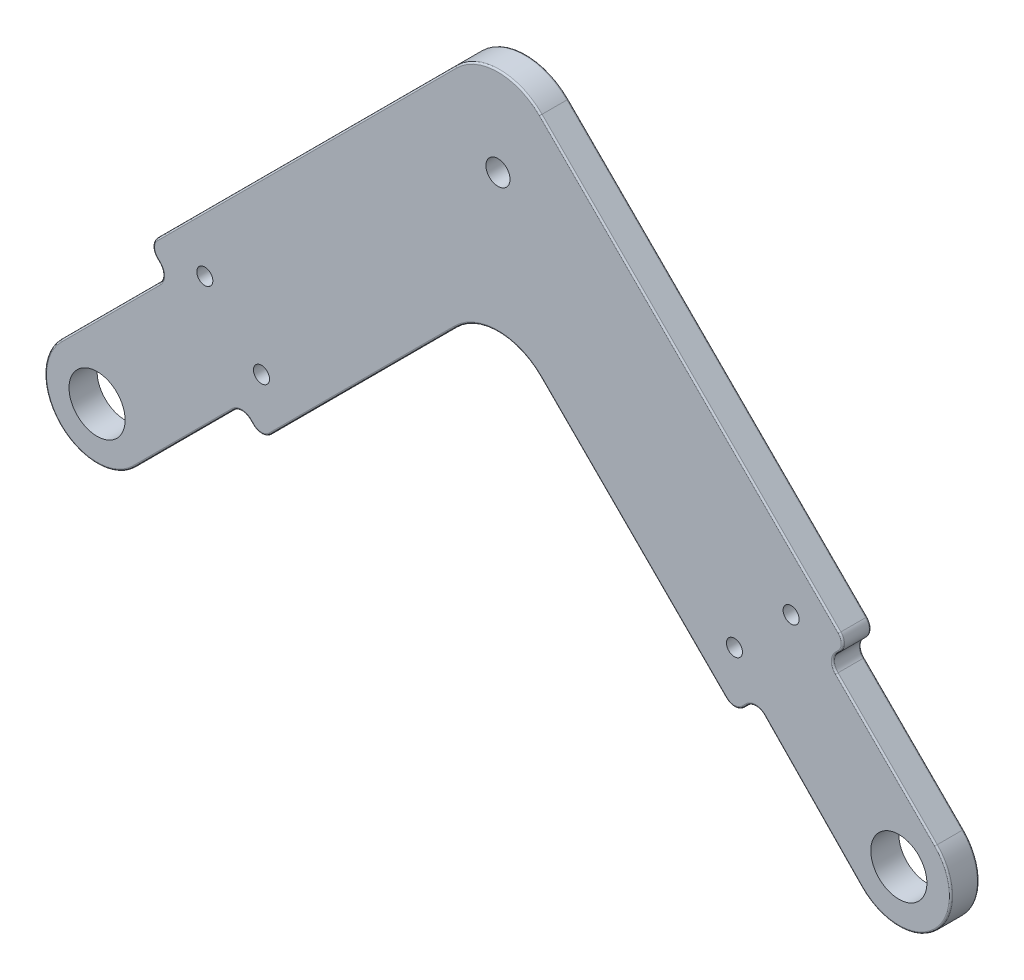
SolidWorks part; units mm, degrees
ref_plane "Front Plane" through (0, 0, 0) normal (0, 0, 1) x (1, 0, 0)
ref_plane "Top Plane" through (0, 0, 0) normal (0, 1, 0) x (1, 0, 0)
ref_plane "Right Plane" through (0, 0, 0) normal (1, 0, 0) x (0, 0, -1)
sketch "Sketch1" plane through (0, 0, 0) normal (0, 0, 1) x (1, 0, 0)
  line L0 (-100, 0) -> (100, 0) construction
  line L1 (-100, 0) -> (0, 100) construction
  line L2 (0, 100) -> (100, 0) construction
  line L3 (0, 0) -> (-50, 50) construction
  line L4 (-40, 60) -> (40, 60) construction
  line L5 (0, 100) -> (0, 60) construction
  circle A0 centre (-100, 0) radius 20
  circle A1 centre (0, 0) radius 20
  circle A2 centre (100, 0) radius 20
  point P4 (0, 0)
  dimension "D5" = 40
  dimension "D1" = 200
  dimension "D2" = 90
  dimension "D3" = 90
  dimension "D4" = 80
sketch "Sketch2" plane through (0, 0, 0) normal (0, 0, 1) x (1, 0, 0)
  line L0 (-56.5165, 43.4835) -> (-40, 60) construction
  line L1 (-100, 0) -> (0, 100) construction
  line L2 (-40, 60) -> (40, 60) construction
  line L3 (40, 60) -> (86.565, 13.435) construction
  line L4 (0, 100) -> (100, 0) construction
  line L5 (-49.4454, 36.4124) -> (-35.8579, 50)
  line L6 (-35.8579, 50) -> (35.8579, 50)
  line L7 (35.8579, 50) -> (79.4939, 6.364)
  line L8 (-63.5876, 50.5546) -> (-44.1421, 70)
  line L9 (-44.1421, 70) -> (44.1421, 70)
  line L10 (44.1421, 70) -> (93.636, 20.5061)
  line L11 (-63.5876, 50.5546) -> (-49.4454, 36.4124)
  line L12 (93.636, 20.5061) -> (79.4939, 6.364)
  line L13 (91.1612, 18.0312) -> (104.5962, 4.5962)
  line L14 (81.9688, 8.8388) -> (95.4038, -4.5962)
  line L15 (75.9584, 9.8995) -> (90.1005, 24.0416) construction
  line L16 (0, 100) -> (0, 60) construction
  line L17 (-6, 70) -> (-3.4304, 82.6944)
  line L18 (6, 70) -> (3.4304, 82.6944)
  circle A0 centre (100, 0) radius 3.5
  circle A1 centre (100, 0) radius 10 construction
  arc A2 (95.4038, -4.5962) -> (104.5962, 4.5962) centre (100, 0) ccw
  circle A3 centre (79.4939, 13.435) radius 1
  circle A4 centre (100, 0) radius 6.5 construction
  circle A5 centre (86.565, 20.5061) radius 1
  circle A6 centre (0, 60) radius 1.5
  circle A7 centre (0, 82) radius 1.5
  arc A8 (3.4304, 82.6944) -> (-3.4304, 82.6944) centre (0, 82) ccw
  circle A9 centre (-50, 50) radius 1.5
  circle A10 centre (0, 82) radius 3.5 construction
  point P25 (106.5, 0)
  point P47 (3.5, 82)
  dimension "D4" = 7
  dimension "D5" = 20
  dimension "D9" = 2
  dimension "D12" = 3
  dimension "D17" = 3
  dimension "D3" = 27.5
  dimension "D7" = 19
  dimension "D8" = 5
  dimension "D10" = 5
  dimension "D11" = 5
  dimension "D13" = 12
  dimension "D15" = 6
  dimension "D16" = 6
  dimension "D1" = 10
  dimension "D2" = 10
  dimension "D6" = 3
  dimension "D14" = 2
sketch "Sketch3" plane through (0, 0, 0) normal (0, 0, 1) x (1, 0, 0)
  line L0 (-100, 0) -> (100, 0) construction
  line L1 (-86.565, 13.435) -> (-50, 50) construction
  line L2 (-100, 0) -> (0, 100) construction
  line L3 (-50, 50) -> (-13.435, 13.435) construction
  line L4 (0, 0) -> (-50, 50) construction
  line L5 (-79.4939, 6.364) -> (-50, 35.8579)
  line L6 (-50, 35.8579) -> (-20.5061, 6.364)
  line L7 (-93.636, 20.5061) -> (-50, 64.1421)
  line L8 (-50, 64.1421) -> (-6.364, 20.5061)
  line L9 (-6.364, 20.5061) -> (-20.5061, 6.364)
  line L10 (-93.636, 20.5061) -> (-79.4939, 6.364)
  line L11 (-91.1612, 18.0312) -> (-104.5962, 4.5962)
  line L12 (-81.9688, 8.8388) -> (-95.4038, -4.5962)
  line L13 (-4.6576, -4.534) -> (-17.8509, 9.0191)
  line L14 (4.5962, 4.5962) -> (-8.8388, 18.0312)
  line L15 (-90.1005, 24.0416) -> (-75.9584, 9.8995) construction
  line L16 (-24.0416, 9.8995) -> (-9.8995, 24.0416) construction
  circle A0 centre (-100, 0) radius 3.5
  circle A1 centre (0, 0) radius 3.5
  circle A2 centre (-100, 0) radius 10 construction
  circle A3 centre (0, 0) radius 10 construction
  arc A4 (-4.6576, -4.534) -> (4.5962, 4.5962) centre (0, 0) ccw
  arc A5 (-104.5962, 4.5962) -> (-95.4038, -4.5962) centre (-100, 0) ccw
  circle A6 centre (0, 0) radius 20 construction
  circle A7 centre (-100, 0) radius 6.5 construction
  circle A8 centre (-86.565, 20.5061) radius 1
  circle A9 centre (0, 0) radius 6.5 construction
  circle A10 centre (-79.4939, 13.435) radius 1
  circle A11 centre (-20.5061, 13.435) radius 1
  circle A12 centre (-13.435, 20.5061) radius 1
  point P28 (-93.5, 0)
  point P36 (6.5, 0)
  dimension "D1" = 20
  dimension "D2" = 7
  dimension "D8" = 2
  dimension "D12" = 2
  dimension "D6" = 19
  dimension "D7" = 19
  dimension "D9" = 5
  dimension "D10" = 5
  dimension "D11" = 5
  dimension "D13" = 5
  dimension "D14" = 5
  dimension "D15" = 5
  dimension "D3" = 3
  dimension "D4" = 10
  dimension "D5" = 10
sketch "Sketch4" plane through (0, 0, 0) normal (0, 0, 1) x (1, 0, 0)
  line L0 (-57.5, 90.5) -> (57.5, 90.5)
  line L1 (4, 60) -> (4, 70)
  line L2 (57.5, 90.5) -> (57.5, 80.5)
  line L3 (57.5, 80.5) -> (44.1421, 70)
  line L4 (-44.1421, 70) -> (-57.5, 80.5)
  line L5 (-57.5, 80.5) -> (-57.5, 90.5)
  line L6 (-44.1421, 70) -> (44.1421, 70) construction
  line L7 (-4, 60) -> (-4, 70)
  line L8 (-22.5, 82) -> (22.5, 82) construction
  line L9 (-22.5, 86.5) -> (22.5, 86.5)
  line L10 (-22.5, 77.5) -> (22.5, 77.5)
  circle A2 centre (0, 60) radius 4
  arc A3 (-4, 60) -> (4, 60) centre (0, 60) ccw
  arc A4 (-22.5, 86.5) -> (-22.5, 77.5) centre (-22.5, 82) ccw
  arc A5 (22.5, 77.5) -> (22.5, 86.5) centre (22.5, 82) ccw
  point P4 (0, 100)
  point P14 (0, 82)
  point P27 (0, 90.5)
  dimension "D5" = 9
  dimension "D1" = 115
  dimension "D2" = 10
  dimension "D4" = 45
  dimension "D6" = 4
  dimension "D3" = 2.5
sketch "Sketch5" plane through (0, 0, 0) normal (0, 0, 1) x (1, 0, 0)
  line L0 (-91.1612, 18.0312) -> (-104.5962, 4.5962) construction
  line L1 (-81.9688, 8.8388) -> (-95.4038, -4.5962) construction
  line L2 (4.5962, 4.5962) -> (-8.8388, 18.0312) construction
  line L3 (-4.6576, -4.534) -> (-17.8509, 9.0191) construction
  line L4 (-91.1612, 18.0312) -> (-104.5962, 4.5962)
  line L5 (-81.9688, 8.8388) -> (-95.4038, -4.5962)
  line L6 (-79.4939, 6.364) -> (-50, 35.8579)
  line L7 (-50, 35.8579) -> (-20.5061, 6.364)
  line L8 (-20.5061, 6.364) -> (-6.364, 20.5061)
  line L9 (-6.364, 20.5061) -> (-50, 64.1421)
  line L10 (-50, 64.1421) -> (-93.636, 20.5061)
  line L11 (-93.636, 20.5061) -> (-79.4939, 6.364)
  line L12 (-79.4939, 6.364) -> (-50, 35.8579)
  line L13 (-50, 35.8579) -> (-20.5061, 6.364)
  line L14 (-20.5061, 6.364) -> (-17.8509, 9.0191)
  line L15 (-6.364, 20.5061) -> (-50, 64.1421)
  line L16 (-50, 64.1421) -> (-93.636, 20.5061)
  line L17 (-93.636, 20.5061) -> (-91.1612, 18.0312)
  line L18 (4.5962, 4.5962) -> (-8.8388, 18.0312)
  line L19 (-4.6576, -4.534) -> (-17.8509, 9.0191)
  line L20 (-81.9688, 8.8388) -> (-79.4939, 6.364)
  line L21 (-8.8388, 18.0312) -> (-6.364, 20.5061)
  arc A0 (-104.5962, 4.5962) -> (-95.4038, -4.5962) centre (-100, 0) ccw construction
  circle A1 centre (0, 0) radius 3.5
  circle A2 centre (0, 0) radius 3.5
  circle A3 centre (-100, 0) radius 3.5
  circle A4 centre (-100, 0) radius 3.5
  circle A5 centre (-79.4939, 13.435) radius 1
  circle A6 centre (-79.4939, 13.435) radius 1
  circle A7 centre (-86.565, 20.5061) radius 1
  circle A8 centre (-86.565, 20.5061) radius 1
  circle A9 centre (-13.435, 20.5061) radius 1
  circle A10 centre (-13.435, 20.5061) radius 1
  circle A11 centre (-20.5061, 13.435) radius 1
  circle A12 centre (-20.5061, 13.435) radius 1
  arc A13 (-4.6576, -4.534) -> (4.5962, 4.5962) centre (0, 0) ccw construction
  arc A14 (-104.5962, 4.5962) -> (-95.4038, -4.5962) centre (-100, 0) ccw
  arc A15 (-4.6576, -4.534) -> (4.5962, 4.5962) centre (0, 0) ccw
  circle A16 centre (-50, 50) radius 1.5 construction
  circle A17 centre (-50, 50) radius 1.5
  dimension "D1" = 0
  dimension "D2" = 0
  dimension "D3" = 0
  dimension "D4" = 0
  dimension "D5" = 0
  dimension "D6" = 0
  dimension "D7" = 0
extrude "Boss-Extrude1" add sketch "Sketch5" along normal blind 3.5
fillet "Fillet1" radius 7.5 2 edges at (-50, 35.8579, 1.75) (-50, 64.1421, 1.75)
fillet "Fillet2" radius 1.5 8 edges at (-93.636, 20.5061, 1.75) (-91.1612, 18.0312, 1.75) (-79.4939, 6.364, 1.75) (-81.9688, 8.8388, 1.75) (-8.8388, 18.0312, 1.75) (-6.364, 20.5061, 1.75) (-17.8509, 9.0191, 1.75) (-20.5061, 6.364, 1.75)
fillet "Fillet3" radius 0.2 48 edges at (-50, 61.0355, 0) (-26.0607, 40.2028, 0) (-6.9853, 20.5061, 0) (-7.6014, 19.2687, 0) (-8.2175, 18.0312, 0) (-1.591, 10.7834, 0) (4.5652, -4.627, 0) (-10.724, 1.6979, 0) (-17.8552, 8.3834, 0) (-19.1857, 7.6844, 0) (-20.5061, 6.9853, 0) (-33.1317, 18.9896, 0) (-50, 32.7513, 0) (-66.8683, 18.9896, 0) (-79.4939, 6.9853, 0) (-80.7313, 7.6014, 0) (-81.9688, 8.2175, 0) (-89.2166, 1.591, 0) (-104.5962, -4.5962, 0) (-98.409, 10.7834, 0) (-91.7825, 18.0312, 0) (-92.3986, 19.2687, 0) (-93.0147, 20.5061, 0) (-50, 61.0355, 3.5) (-26.0607, 40.2028, 3.5) (-6.9853, 20.5061, 3.5) (-7.6014, 19.2687, 3.5) (-8.2175, 18.0312, 3.5) (-1.591, 10.7834, 3.5) (4.5652, -4.627, 3.5) (-10.724, 1.6979, 3.5) (-17.8552, 8.3834, 3.5) (-19.1857, 7.6844, 3.5) (-20.5061, 6.9853, 3.5) (-33.1317, 18.9896, 3.5) (-50, 32.7513, 3.5) (-66.8683, 18.9896, 3.5) (-79.4939, 6.9853, 3.5) (-80.7313, 7.6014, 3.5) (-81.9688, 8.2175, 3.5) (-89.2166, 1.591, 3.5) (-104.5962, -4.5962, 3.5) (-98.409, 10.7834, 3.5) (-91.7825, 18.0312, 3.5) (-92.3986, 19.2687, 3.5) (-93.0147, 20.5061, 3.5) (-73.9393, 40.2028, 0) (-73.9393, 40.2028, 3.5)
